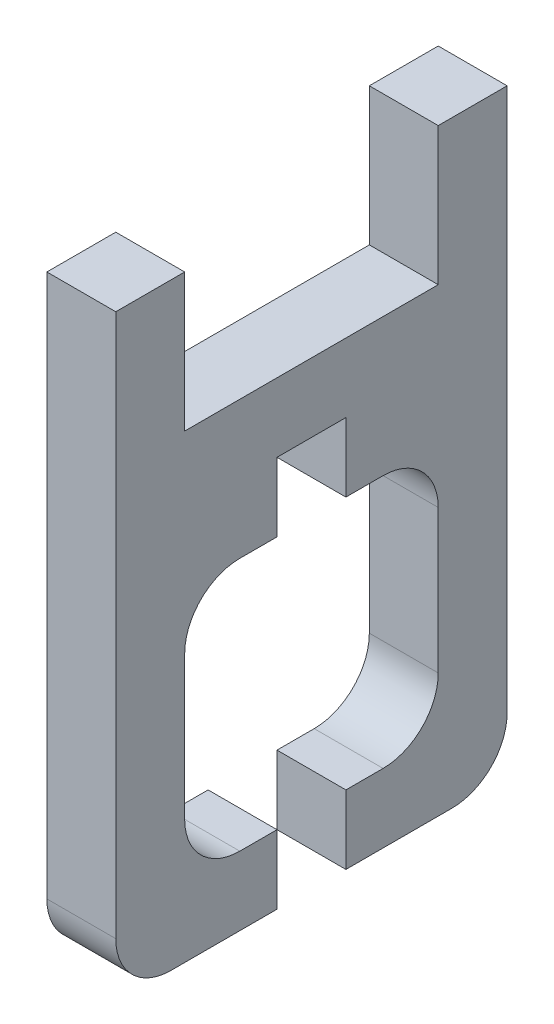
SolidWorks part; units mm, degrees
material "Pine"
ref_plane "Front Plane" through (0, 0, 0) normal (0, 0, 1) x (1, 0, 0)
ref_plane "Top Plane" through (0, 0, 0) normal (0, 1, 0) x (1, 0, 0)
ref_plane "Right Plane" through (0, 0, 0) normal (1, 0, 0) x (0, 0, -1)
sketch "Sketch2" plane through (0, 0, 0) normal (1, 0, 0) x (0, 0, -1)
  line L7 (30.988, 0) -> (5.08, 0)
  line L9 (11.43, 6.35) -> (24.638, 6.35)
  line L10 (6.35, 11.43) -> (6.35, 24.638)
  line L12 (29.718, 11.43) -> (29.718, 24.638)
  line L18 (36.068, 36.068) -> (36.068, 5.08)
  line L21 (0, 36.068) -> (0, 5.08)
  line L24 (24.638, 29.718) -> (21.209, 29.718)
  line L25 (21.209, 29.718) -> (21.209, 36.068)
  line L26 (21.209, 36.068) -> (14.859, 36.068)
  line L27 (14.859, 36.068) -> (14.859, 29.718)
  line L28 (14.859, 29.718) -> (11.43, 29.718)
  line L29 (0, 36.068) -> (0, 55.118)
  line L30 (14.859, 6.35) -> (21.209, 6.35)
  line L31 (14.859, 6.35) -> (14.859, 0)
  line L32 (14.859, 0) -> (21.209, 0)
  line L33 (21.209, 6.35) -> (21.209, 0)
  line L34 (0, 55.118) -> (6.35, 55.118)
  line L35 (6.35, 55.118) -> (6.35, 42.418)
  line L39 (36.068, 55.118) -> (36.068, 36.068)
  line L40 (36.068, 55.118) -> (29.718, 55.118)
  line L41 (29.718, 55.118) -> (29.718, 42.418)
  line L42 (29.718, 42.418) -> (6.35, 42.418)
  arc A0 (11.43, 6.35) -> (6.35, 11.43) centre (11.43, 11.43) cw
  arc A1 (24.638, 6.35) -> (29.718, 11.43) centre (24.638, 11.43) ccw
  arc A2 (24.638, 29.718) -> (29.718, 24.638) centre (24.638, 24.638) cw
  arc A3 (6.35, 24.638) -> (11.43, 29.718) centre (11.43, 24.638) cw
  arc A4 (36.068, 5.08) -> (30.988, 0) centre (30.988, 5.08) cw
  arc A5 (0, 5.08) -> (5.08, 0) centre (5.08, 5.08) ccw
  point P13 (18.034, 42.418)
  point P16 (18.034, 0)
  point P26 (18.034, 0)
  point P30 (6.35, 6.35)
  point P35 (29.718, 29.718)
  point P38 (6.35, 29.718)
  point P43 (0, 0)
  dimension "D15" = 5.08
  dimension "D16" = 5.08
  dimension "D2" = 23.368
  dimension "D3" = 23.368
  dimension "D4" = 6.35
  dimension "D9" = 6.35
  dimension "D10" = 6.35
  dimension "D7" = 6.35
  dimension "D8" = 6.35
  dimension "D14" = 6.35
  dimension "D5" = 6.35
  dimension "D6" = 6.35
extrude "Boss-Extrude1" add sketch "Sketch2" along normal blind 6.35
equation "\"D2@Sketch2\"=\"D3@Sketch2\""
